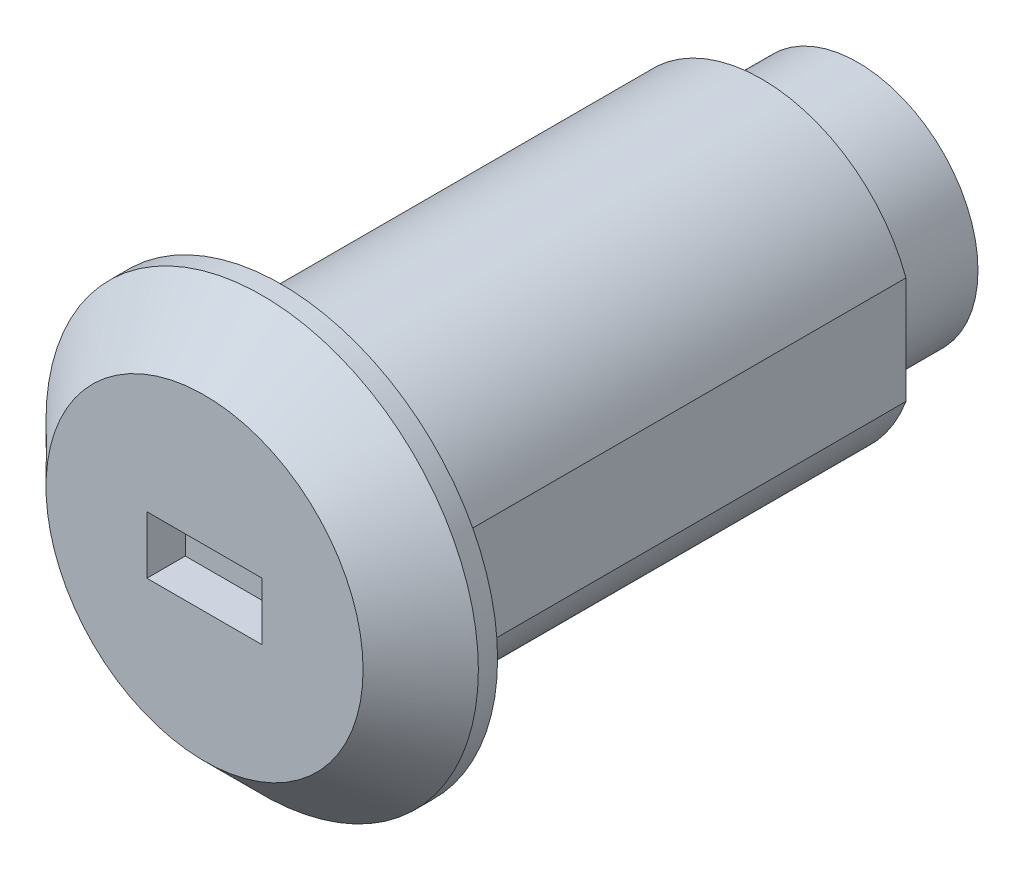
SolidWorks part; units mm, degrees
ref_plane "前视基准面" through (0, 0, 0) normal (0, 0, 1) x (1, 0, 0)
ref_plane "上视基准面" through (0, 0, 0) normal (0, 1, 0) x (1, 0, 0)
ref_plane "右视基准面" through (0, 0, 0) normal (1, 0, 0) x (0, 0, -1)
sketch "草图1" plane through (0, 0, 0) normal (0, 0, 1) x (1, 0, 0)
  line L0 (0, 0) -> (0, 36.6059) construction
  line L1 (0, 36.6059) -> (0, -30.2559) construction
  line L2 (-35.8588, 0) -> (29.1353, 0) construction
  circle A0 centre (0, 0) radius 11.25
  dimension "D1" = 22.5
extrude "拉伸1" add sketch "草图1" along normal blind 4
chamfer "倒角1" distance 3 angle 45 1 edges at (11.25, 0, 4)
sketch "草图2" plane through (0, 0, 4) normal (0, 0, 1) x (1, 0, 0)
  line L0 (-6.6609, 0) -> (5.0173, 0) construction
  line L1 (0, 5.7093) -> (0, -4.7145) construction
  line L3 (-3, 1.5) -> (3, 1.5)
  line L4 (-3, 1.5) -> (-3, -1.5)
  line L5 (-3, -1.5) -> (3, -1.5)
  line L6 (3, 1.5) -> (3, -1.5)
  dimension "D1" = 6
  dimension "D2" = 3
extrude "切除-拉伸1" cut sketch "草图2" against normal blind 2
sketch "草图3" plane through (0, 0, 0) normal (0, 0, -1) x (-1, 0, 0)
  line L0 (0, 13.2042) -> (0, -14.0761) construction
  line L1 (-13.3287, 0) -> (13.6401, 0) construction
  line L2 (-7.5, 2.7839) -> (-7.5, -2.7839)
  line L3 (7.5, 2.7839) -> (7.5, -2.7839)
  arc A0 (-7.5, -2.7839) -> (7.5, -2.7839) centre (0, 0) ccw
  arc A1 (7.5, 2.7839) -> (-7.5, 2.7839) centre (0, 0) ccw
  dimension "D1" = 16
  dimension "D2" = 15
extrude "拉伸2" add sketch "草图3" along normal blind 25
sketch "草图4" plane through (0, 0, -25) normal (0, 0, -1) x (-1, 0, 0)
  circle A0 centre (0, 0) radius 6.25
  dimension "D1" = 12.5
extrude "拉伸3" add sketch "草图4" along normal blind 5
